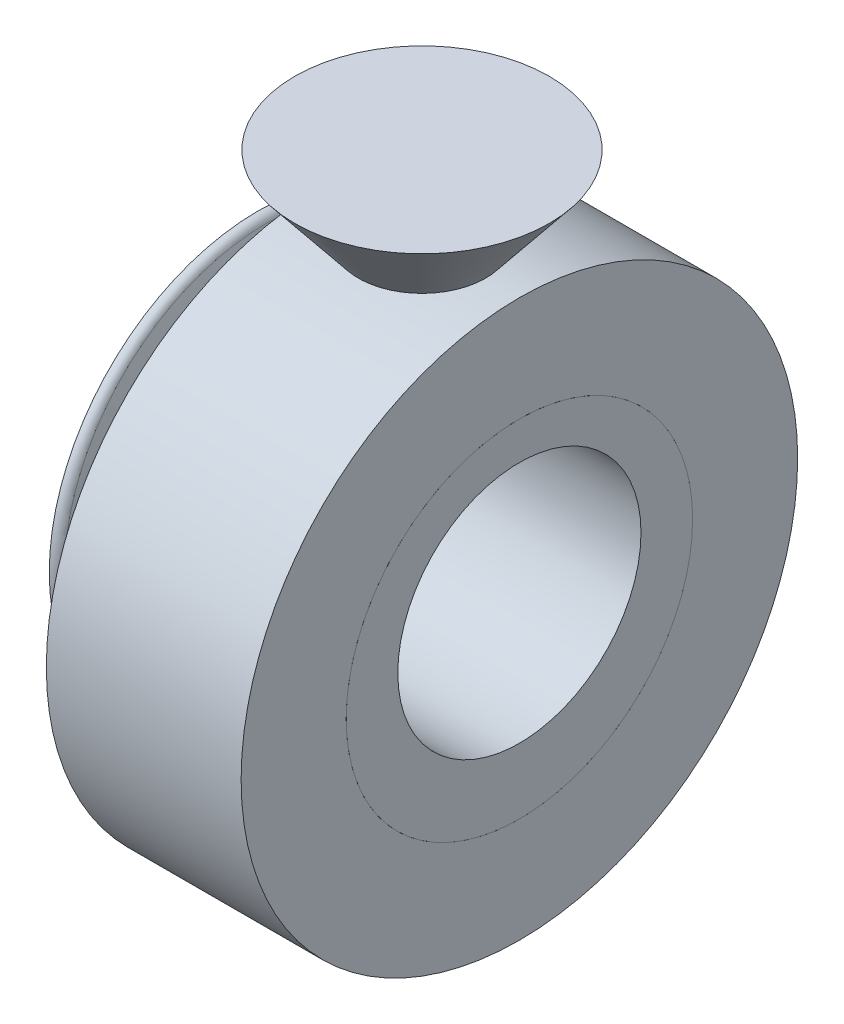
SolidWorks part; units mm, degrees
material "ABS"
ref_plane "Front Plane" through (0, 0, 0) normal (0, 0, 1) x (1, 0, 0)
ref_plane "Top Plane" through (0, 0, 0) normal (0, 1, 0) x (1, 0, 0)
ref_plane "Right Plane" through (0, 0, 0) normal (1, 0, 0) x (0, 0, -1)
sketch "Sketch2" plane through (0, 0, 0) normal (1, 0, 0) x (0, 0, -1)
  circle A0 centre (0, 0) radius 15.8115
  circle A1 centre (0, 1.27) radius 11.1
  point P5 (0, 0)
  dimension "D1" = 22.2
  dimension "D2" = 31.623
  dimension "D3" = 1.27
extrude "Boss-Extrude1" add sketch "Sketch2" along normal blind 17.78
sketch "Sketch3" plane through (0, 0, 0) normal (0, 0, 1) x (1, 0, 0)
  line L0 (0, 10.27) -> (0, 20.32)
  line L1 (0, 15.8115) -> (0, -15.8115) construction
  line L2 (-5.3107, 19.7271) -> (-4.6089, 17.108)
  line L3 (-3.3099, 16.82) -> (-0.6128, 20.0342)
  line L4 (-6.0834, 20.32) -> (-6.0834, 10.27)
  line L5 (-6.0834, 10.27) -> (0, 10.27)
  line L6 (8.89, 12.37) -> (8.89, -9.83) construction
  line L7 (17.78, 12.37) -> (0, 12.37) construction
  line L8 (0, -9.83) -> (17.78, -9.83) construction
  line L9 (8.89, 1.27) -> (-15.4743, 1.27) construction
  arc A0 (-6.0834, 20.32) -> (-5.3107, 19.7271) centre (-6.0834, 19.52) cw
  arc A1 (-4.6089, 17.108) -> (-3.3099, 16.82) centre (-3.8844, 17.3021) ccw
  arc A2 (-0.6128, 20.0342) -> (0, 20.32) centre (0, 19.52) cw
  point P21 (8.89, 1.27)
  dimension "D1" = 9
  dimension "D4" = 0.8
  dimension "D5" = 0.75
  dimension "D2" = 19.05
  dimension "D3" = 3.5
  dimension "D6" = 40
  dimension "D7" = 15
revolve "Revolve1" add sketch "Sketch3" angle 360 about L9
sketch "Sketch4" plane through (0, 0, 0) normal (0, 1, 0) x (1, 0, 0)
  line L0 (8.89, 15.8115) -> (8.89, 0) construction
  line L1 (17.78, 15.8115) -> (0, 15.8115) construction
  circle A0 centre (8.89, 0) radius 4.826
  point P2 (0, 0)
  dimension "D1" = 9.652
extrude "Cut-Extrude1" cut sketch "Sketch4" along normal blind 17.78
sketch "Sketch5" plane through (0, 0, 0) normal (1, 0, 0) x (0, 0, -1)
  circle A0 centre (0, 0) radius 15.8115
  circle A1 centre (0, 0) radius 15.8115 construction
  circle A2 centre (0, 0) radius 25.4
  dimension "D1" = 50.8
extrude "Boss-Extrude2" add sketch "Sketch5" along normal up to surface (17.78 mm away) separate body up to face at (17.78, 0, -15.8115)
sketch "Sketch6" plane through (0, 0, 0) normal (0, 0, 1) x (1, 0, 0)
  line L0 (8.89, 25.4) -> (8.89, 32.639)
  line L2 (17.78, 25.4) -> (0, 25.4) construction
  line L3 (8.89, 32.639) -> (20.5159, 32.639)
  line L4 (20.5159, 32.639) -> (14.7029, 25.4)
  line L5 (14.7029, 25.4) -> (8.89, 25.4)
  dimension "D1" = 58.039
revolve "Revolve2" add sketch "Sketch6" angle 360 about L0
ref_plane "Plane1" through (5.8483, 0, 0) normal (1, 0, 0) x (0, 0, -1)
